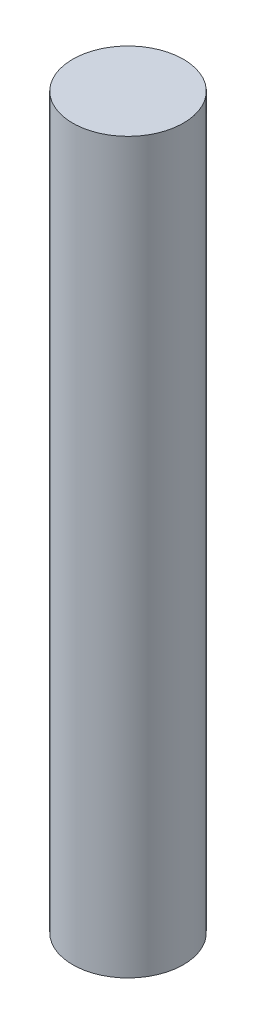
SolidWorks part; units mm, degrees
ref_plane "Front Plane" through (0, 0, 0) normal (0, 0, 1) x (1, 0, 0)
ref_plane "Top Plane" through (0, 0, 0) normal (0, 1, 0) x (1, 0, 0)
ref_plane "Right Plane" through (0, 0, 0) normal (1, 0, 0) x (0, 0, -1)
sketch "Sketch1" plane through (0, 0, 0) normal (0, 1, 0) x (1, 0, 0)
  circle A0 centre (0, 0) radius 3.95
  dimension "D1" = 7.9
extrude "Boss-Extrude1" add sketch "Sketch1" along normal blind 52
